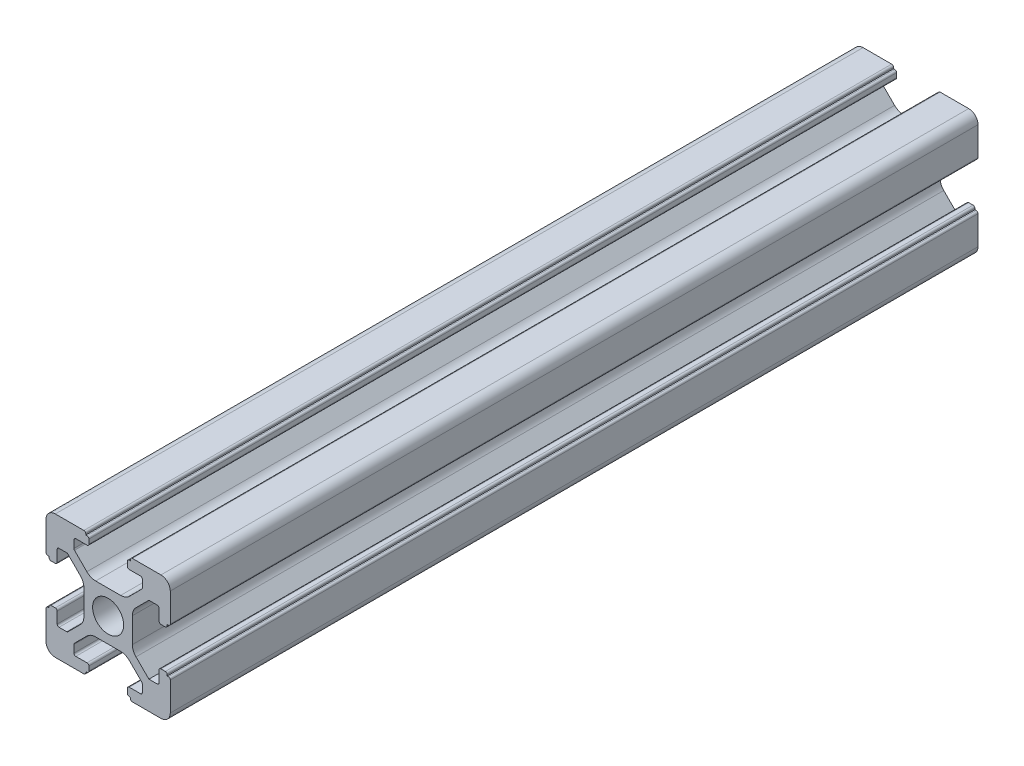
SolidWorks part; units mm, degrees
ref_plane "前视基准面" through (0, 0, 0) normal (0, 0, 1) x (1, 0, 0)
ref_plane "上视基准面" through (0, 0, 0) normal (0, 1, 0) x (1, 0, 0)
ref_plane "右视基准面" through (0, 0, 0) normal (1, 0, 0) x (0, 0, -1)
sketch "草图1" plane through (0, 0, 0) normal (0, 0, 1) x (1, 0, 0)
  line L0 (3.9, 0) -> (3.9, -2.0109)
  line L1 (4.4858, -3.4251) -> (6.5607, -5.5)
  line L2 (6.5607, -5.5) -> (7.9, -5.5)
  line L3 (8.2, -5.2) -> (8.2, -3.4)
  line L4 (8.5, -3.1) -> (9.2, -3.1)
  line L5 (9.5, -3.4) -> (9.5, -3.6)
  line L6 (9.5, -3.6) -> (9.7, -3.6)
  line L7 (10, -3.9) -> (10, -8.5)
  line L8 (8.5, -10) -> (3.9, -10)
  line L9 (3.1, -9.2) -> (3.1, -8.5)
  line L10 (3.4, -8.2) -> (5.2, -8.2)
  line L11 (5.5, -7.9) -> (5.5, -6.6849)
  line L12 (5.4121, -6.4728) -> (3.4251, -4.4858)
  line L13 (2.0109, -3.9) -> (0, -3.9)
  line L14 (0, -3.9) -> (-2.0109, -3.9)
  line L15 (-3.4251, -4.4858) -> (-5.4121, -6.4728)
  line L16 (-5.5, -6.6849) -> (-5.5, -7.9)
  line L17 (-5.2, -8.2) -> (-3.4, -8.2)
  line L18 (-3.1, -8.5) -> (-3.1, -9.2)
  line L19 (-3.9, -10) -> (-8.5, -10)
  line L20 (-10, -8.5) -> (-10, -3.9)
  line L21 (-9.7, -3.6) -> (-9.5, -3.6)
  line L22 (-9.5, -3.6) -> (-9.5, -3.4)
  line L23 (-9.2, -3.1) -> (-8.5, -3.1)
  line L24 (-8.2, -3.4) -> (-8.2, -5.2)
  line L25 (-7.9, -5.5) -> (-6.6849, -5.5)
  line L26 (-6.4728, -5.4121) -> (-4.4858, -3.4251)
  line L27 (-3.9, -2.0109) -> (-3.9, 0)
  line L28 (-3.9, 0) -> (-3.9, 2.0109)
  line L29 (-4.4858, 3.4251) -> (-6.4728, 5.4121)
  line L30 (-6.6849, 5.5) -> (-7.9, 5.5)
  line L31 (-8.2, 5.2) -> (-8.2, 3.4)
  line L32 (-8.5, 3.1) -> (-9.2, 3.1)
  line L33 (-9.5, 3.4) -> (-9.5, 3.6)
  line L34 (-9.5, 3.6) -> (-9.7, 3.6)
  line L35 (-10, 3.9) -> (-10, 8.5)
  line L36 (-8.5, 10) -> (-3.9, 10)
  line L37 (-3.6, 9.7) -> (-3.6, 9.5)
  line L38 (-3.6, 9.5) -> (-3.4, 9.5)
  line L39 (-3.1, 9.2) -> (-3.1, 8.5)
  line L40 (-3.4, 8.2) -> (-5.2, 8.2)
  line L41 (-5.5, 7.9) -> (-5.5, 6.6849)
  line L42 (-5.4121, 6.4728) -> (-3.4251, 4.4858)
  line L43 (-2.0109, 3.9) -> (0, 3.9)
  line L44 (0, 3.9) -> (2.0109, 3.9)
  line L45 (3.4251, 4.4858) -> (5.4121, 6.4728)
  line L46 (5.5, 6.6849) -> (5.5, 7.9)
  line L47 (5.2, 8.2) -> (3.4, 8.2)
  line L48 (3.1, 8.5) -> (3.1, 9.2)
  line L49 (3.4, 9.5) -> (3.6, 9.5)
  line L50 (3.6, 9.5) -> (3.6, 9.7)
  line L51 (3.9, 10) -> (8.5, 10)
  line L52 (10, 8.5) -> (10, 3.9)
  line L53 (9.7, 3.6) -> (9.5, 3.6)
  line L54 (9.5, 3.6) -> (9.5, 3.4)
  line L55 (9.2, 3.1) -> (8.5, 3.1)
  line L56 (8.2, 3.4) -> (8.2, 5.2)
  line L57 (7.9, 5.5) -> (6.6849, 5.5)
  line L58 (6.4728, 5.4121) -> (4.4858, 3.4251)
  line L59 (3.9, 2.0109) -> (3.9, 0)
  circle A0 centre (0, 0) radius 2.5
  arc A1 (3.9, -2.0109) -> (4.4858, -3.4251) centre (5.9, -2.0109) ccw
  arc A2 (7.9, -5.5) -> (8.2, -5.2) centre (7.9, -5.2) ccw
  arc A3 (8.5, -3.1) -> (8.2, -3.4) centre (8.5, -3.4) ccw
  arc A4 (9.5, -3.4) -> (9.2, -3.1) centre (9.2, -3.4) ccw
  arc A5 (10, -3.9) -> (9.7, -3.6) centre (9.7, -3.9) ccw
  arc A6 (8.5, -10) -> (10, -8.5) centre (8.5, -8.5) ccw
  arc A7 (3.6, -9.7) -> (3.9, -10) centre (3.9, -9.7) ccw
  arc A8 (3.6, -9.7) -> (3.4, -9.5) centre (3.4, -9.7) ccw
  arc A9 (3.1, -9.2) -> (3.4, -9.5) centre (3.4, -9.2) ccw
  arc A10 (3.4, -8.2) -> (3.1, -8.5) centre (3.4, -8.5) ccw
  arc A11 (5.2, -8.2) -> (5.5, -7.9) centre (5.2, -7.9) ccw
  arc A12 (5.5, -6.6849) -> (5.4121, -6.4728) centre (5.2, -6.6849) ccw
  arc A13 (3.4251, -4.4858) -> (2.0109, -3.9) centre (2.0109, -5.9) ccw
  arc A14 (-2.0109, -3.9) -> (-3.4251, -4.4858) centre (-2.0109, -5.9) ccw
  arc A15 (-5.4121, -6.4728) -> (-5.5, -6.6849) centre (-5.2, -6.6849) ccw
  arc A16 (-5.5, -7.9) -> (-5.2, -8.2) centre (-5.2, -7.9) ccw
  arc A17 (-3.1, -8.5) -> (-3.4, -8.2) centre (-3.4, -8.5) ccw
  arc A18 (-3.4, -9.5) -> (-3.1, -9.2) centre (-3.4, -9.2) ccw
  arc A19 (-3.4, -9.5) -> (-3.6, -9.7) centre (-3.4, -9.7) ccw
  arc A20 (-3.9, -10) -> (-3.6, -9.7) centre (-3.9, -9.7) ccw
  arc A21 (-10, -8.5) -> (-8.5, -10) centre (-8.5, -8.5) ccw
  arc A22 (-9.7, -3.6) -> (-10, -3.9) centre (-9.7, -3.9) ccw
  arc A23 (-9.2, -3.1) -> (-9.5, -3.4) centre (-9.2, -3.4) ccw
  arc A24 (-8.2, -3.4) -> (-8.5, -3.1) centre (-8.5, -3.4) ccw
  arc A25 (-8.2, -5.2) -> (-7.9, -5.5) centre (-7.9, -5.2) ccw
  arc A26 (-6.6849, -5.5) -> (-6.4728, -5.4121) centre (-6.6849, -5.2) ccw
  arc A27 (-4.4858, -3.4251) -> (-3.9, -2.0109) centre (-5.9, -2.0109) ccw
  arc A28 (-3.9, 2.0109) -> (-4.4858, 3.4251) centre (-5.9, 2.0109) ccw
  arc A29 (-6.4728, 5.4121) -> (-6.6849, 5.5) centre (-6.6849, 5.2) ccw
  arc A30 (-7.9, 5.5) -> (-8.2, 5.2) centre (-7.9, 5.2) ccw
  arc A31 (-8.5, 3.1) -> (-8.2, 3.4) centre (-8.5, 3.4) ccw
  arc A32 (-9.5, 3.4) -> (-9.2, 3.1) centre (-9.2, 3.4) ccw
  arc A33 (-10, 3.9) -> (-9.7, 3.6) centre (-9.7, 3.9) ccw
  arc A34 (-8.5, 10) -> (-10, 8.5) centre (-8.5, 8.5) ccw
  arc A35 (-3.6, 9.7) -> (-3.9, 10) centre (-3.9, 9.7) ccw
  arc A36 (-3.1, 9.2) -> (-3.4, 9.5) centre (-3.4, 9.2) ccw
  arc A37 (-3.4, 8.2) -> (-3.1, 8.5) centre (-3.4, 8.5) ccw
  arc A38 (-5.2, 8.2) -> (-5.5, 7.9) centre (-5.2, 7.9) ccw
  arc A39 (-5.5, 6.6849) -> (-5.4121, 6.4728) centre (-5.2, 6.6849) ccw
  arc A40 (-3.4251, 4.4858) -> (-2.0109, 3.9) centre (-2.0109, 5.9) ccw
  arc A41 (2.0109, 3.9) -> (3.4251, 4.4858) centre (2.0109, 5.9) ccw
  arc A42 (5.4121, 6.4728) -> (5.5, 6.6849) centre (5.2, 6.6849) ccw
  arc A43 (5.5, 7.9) -> (5.2, 8.2) centre (5.2, 7.9) ccw
  arc A44 (3.1, 8.5) -> (3.4, 8.2) centre (3.4, 8.5) ccw
  arc A45 (3.4, 9.5) -> (3.1, 9.2) centre (3.4, 9.2) ccw
  arc A46 (3.9, 10) -> (3.6, 9.7) centre (3.9, 9.7) ccw
  arc A47 (10, 8.5) -> (8.5, 10) centre (8.5, 8.5) ccw
  arc A48 (9.7, 3.6) -> (10, 3.9) centre (9.7, 3.9) ccw
  arc A49 (9.2, 3.1) -> (9.5, 3.4) centre (9.2, 3.4) ccw
  arc A50 (8.2, 3.4) -> (8.5, 3.1) centre (8.5, 3.4) ccw
  arc A51 (8.2, 5.2) -> (7.9, 5.5) centre (7.9, 5.2) ccw
  arc A52 (6.6849, 5.5) -> (6.4728, 5.4121) centre (6.6849, 5.2) ccw
  arc A53 (4.4858, 3.4251) -> (3.9, 2.0109) centre (5.9, 2.0109) ccw
extrude "凸台-拉伸1" add sketch "草图1" along normal blind 130 contours L42 A40 L43 L44 A41 L45 A42 L46 A43 L47 A44 L48 A45 L49 L50 A46 L51 A47 L52 A48 L53 L54 A49 L55 A50 L56 A51 L57 A52 L58 A53 L59 L0 A1 L1 L2 A2 L3 A3 L4 A4 L5 L6 A5 L7 A6 L8 A7 A8 A9 L9 A10 L10 A11 L11 A12 L12 A13 L13 L14 A14 L15 A15 L16 A16 L17 A17 L18 A18 A19 A20 L19 A21 L20 A22 L21 L22 A23 L23 A24 L24 A25 L25 A26 L26 A27 L27 L28 A28 L29 A29 L30 A30 L31 A31 L32 A32 L33 L34 A33 L35 A34 L36 A35 L37 L38 A36 L39 A37 L40 A38 L41 A39 | A0
